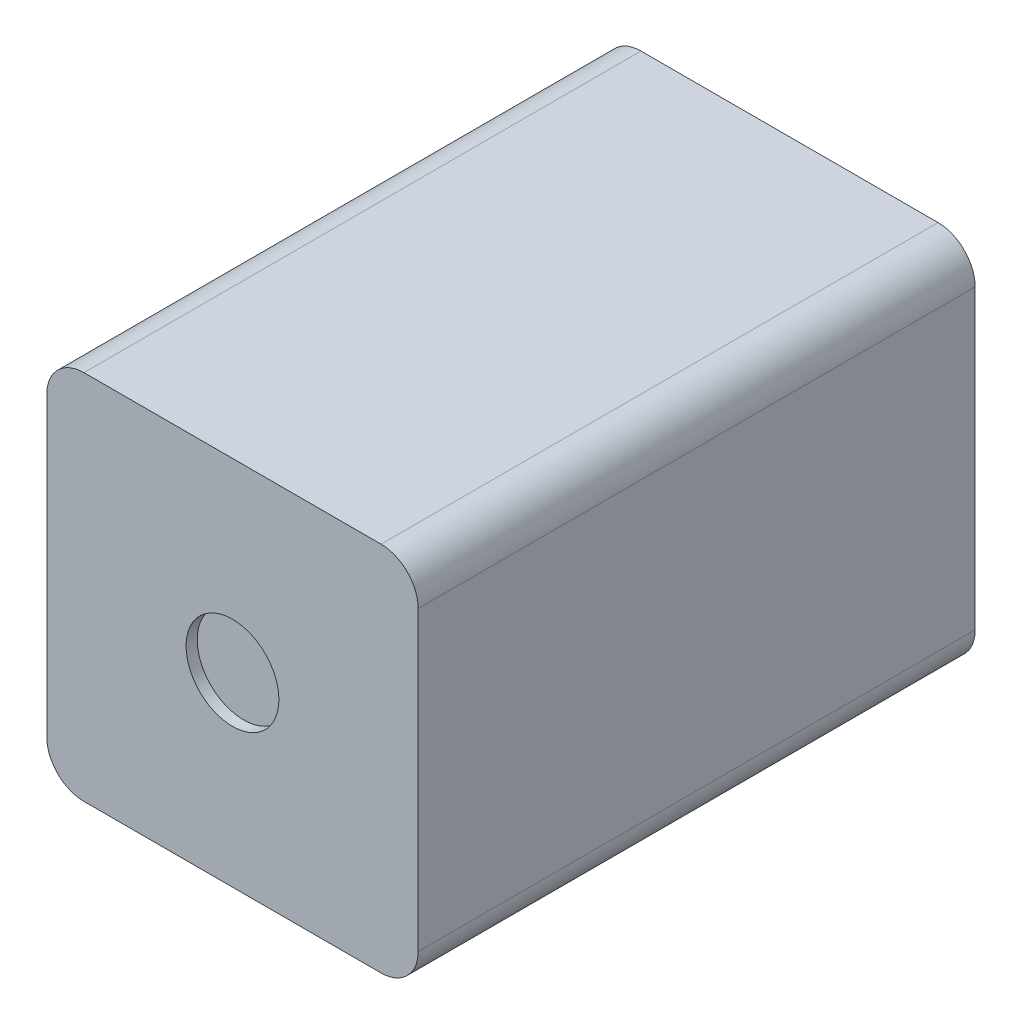
SolidWorks part; units mm, degrees
ref_plane "Front Plane" through (0, 0, 0) normal (0, 0, 1) x (1, 0, 0)
ref_plane "Top Plane" through (0, 0, 0) normal (0, 1, 0) x (1, 0, 0)
ref_plane "Right Plane" through (0, 0, 0) normal (1, 0, 0) x (0, 0, -1)
sketch "Sketch2" plane through (0, 0, 0) normal (0, 0, 1) x (1, 0, 0)
  line L1 (0, 0) -> (-25.4, 0)
  line L2 (0, 0) -> (0, -25.4)
  line L3 (0, -25.4) -> (-25.4, -25.4)
  line L4 (-25.4, 0) -> (-25.4, -25.4)
  dimension "D1" = 25.4
  dimension "D2" = 25.4
extrude "Boss-Extrude1" add sketch "Sketch2" along normal blind 38.1
fillet "Fillet2" radius 2.54 4 edges at (0, -25.4, 19.05) (-25.4, -25.4, 19.05) (0, 0, 19.05) (-25.4, 0, 19.05)
sketch "Sketch3" plane through (0, 0, 38.1) normal (0, 0, 1) x (1, 0, 0)
  line L0 (-12.7, 0) -> (-12.7, -43.9066) construction
  line L1 (-2.54, 0) -> (-22.86, 0) construction
  line L2 (-25.4, -12.7) -> (0, -12.7) construction
  line L3 (-25.4, -2.54) -> (-25.4, -22.86) construction
  line L4 (0, -22.86) -> (0, -2.54) construction
  circle A0 centre (-12.7, -12.7) radius 15.24
  dimension "D1" = 30.48
sketch "Sketch4" plane through (0, 0, 38.1) normal (0, 0, 1) x (1, 0, 0)
  circle A0 centre (-12.7, -12.7) radius 3.175
  dimension "D1" = 6.35
extrude "Cut-Extrude1" cut sketch "Sketch4" against normal blind 0.762
sketch "Sketch5" plane through (0, 0, 0) normal (0, 0, -1) x (-1, 0, 0)
  line L0 (12.7, 0) -> (12.7, -25.4) construction
  line L1 (2.54, 0) -> (22.86, 0) construction
  line L2 (22.86, -25.4) -> (2.54, -25.4) construction
  line L3 (25.4, -12.7) -> (0, -12.7) construction
  line L4 (25.4, -2.54) -> (25.4, -22.86) construction
  line L5 (0, -22.86) -> (0, -2.54) construction
  circle A0 centre (12.7, -12.7) radius 3.175
  dimension "D1" = 6.35
extrude "Cut-Extrude2" cut sketch "Sketch5" against normal blind 0.762
